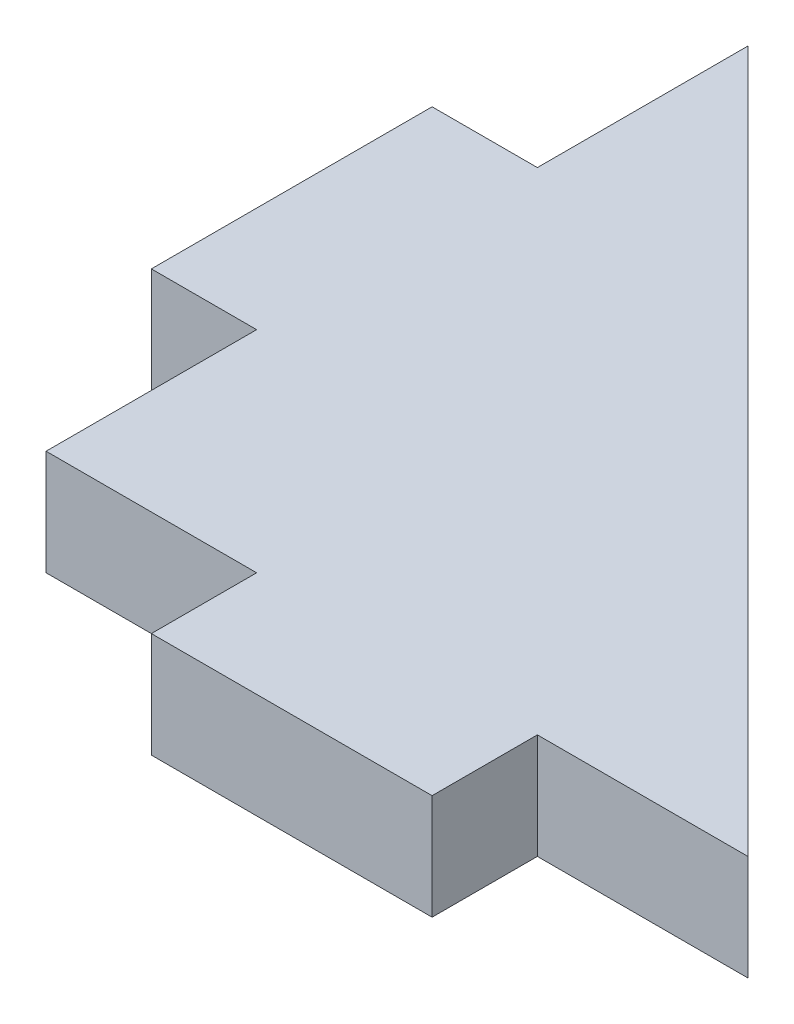
SolidWorks part; units mm, degrees
ref_plane "Alzado" through (0, 0, 0) normal (0, 0, 1) x (1, 0, 0)
ref_plane "Planta" through (0, 0, 0) normal (0, 1, 0) x (1, 0, 0)
ref_plane "Vista lateral" through (0, 0, 0) normal (1, 0, 0) x (0, 0, -1)
sketch "Croquis1" plane through (0, 0, 0) normal (0, 1, 0) x (1, 0, 0)
  line L0 (0, 0) -> (6, 0)
  line L1 (0, 0) -> (0, 6)
  line L2 (0, 20) -> (20, 0)
  line L3 (10, -3) -> (6, -3)
  line L4 (6, -3) -> (6, 0)
  line L5 (10, -3) -> (14, -3)
  line L6 (14, -3) -> (14, 0)
  line L7 (0, 14) -> (0, 20)
  line L8 (-3, 10) -> (-3, 14)
  line L9 (-3, 14) -> (0, 14)
  line L10 (-3, 10) -> (-3, 6)
  line L11 (-3, 6) -> (0, 6)
  line L12 (14, 0) -> (20, 0)
  dimension "D1" = 20
  dimension "D2" = 20
  dimension "D3" = 4
  dimension "D5" = 4
  dimension "D6" = 4
  dimension "D7" = 4
extrude "Saliente-Extruir1" add sketch "Croquis1" along normal blind 3
